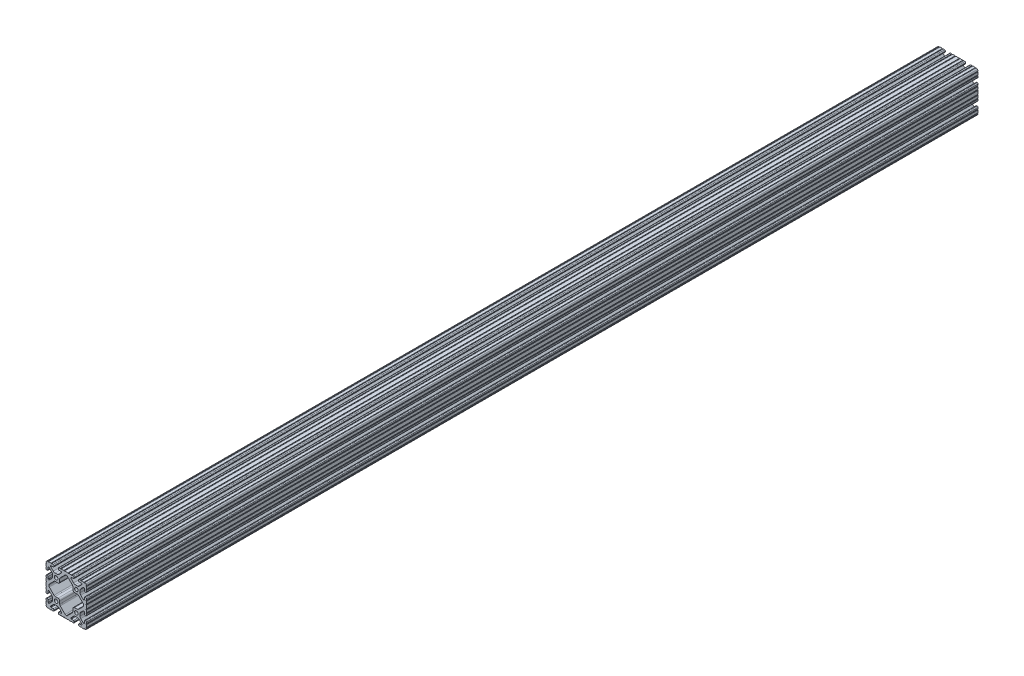
SolidWorks part; units mm, degrees
material "6061-T6 (SS)"
ref_plane "Front" through (0, 0, 0) normal (0, 0, 1) x (1, 0, 0)
ref_plane "Top" through (0, 0, 0) normal (0, 1, 0) x (1, 0, 0)
ref_plane "Right" through (0, 0, 0) normal (1, 0, 0) x (0, 0, -1)
ref_plane "Plane1" through (0, 0, -609.6) normal (0, 0, -1) x (-1, 0, 0)
sketch "Sketch1" plane through (0, 0, -609.6) normal (0, 0, -1) x (-1, 0, 0)
  line L0 (31.9021, -2.4756) -> (23.0141, -11.3637)
  line L1 (20.769, -12.2936) -> (15.4686, -12.2936)
  line L2 (12.2936, -15.4686) -> (12.2936, -20.5983)
  line L3 (11.3637, -22.8433) -> (2.0515, -32.1555)
  line L4 (-2.0515, -32.1555) -> (-11.3637, -22.8433)
  line L5 (-12.2936, -20.5983) -> (-12.2936, -15.4686)
  line L6 (-15.4686, -12.2936) -> (-20.769, -12.2936)
  line L7 (-23.0141, -11.3637) -> (-31.9021, -2.4756)
  line L8 (-31.9021, 2.4756) -> (-23.0141, 11.3637)
  line L9 (-20.769, 12.2936) -> (-15.4686, 12.2936)
  line L10 (-12.2936, 15.4686) -> (-12.2936, 20.5983)
  line L11 (-11.3637, 22.8433) -> (-2.0515, 32.1555)
  line L12 (2.0515, 32.1555) -> (11.3637, 22.8433)
  line L13 (12.2936, 20.5983) -> (12.2936, 15.4686)
  line L14 (15.4686, 12.2936) -> (20.769, 12.2936)
  line L15 (23.0141, 11.3637) -> (31.9021, 2.4756)
  line L16 (36.5252, -23.0554) -> (35.6108, -23.0554)
  line L17 (34.036, -24.6302) -> (34.036, -28.448)
  line L18 (33.147, -29.337) -> (32.6643, -29.337)
  line L19 (32.0357, -29.0766) -> (27.1976, -24.2385)
  line L20 (25.8064, -20.8799) -> (25.8064, -17.2201)
  line L21 (27.1976, -13.8615) -> (31.9489, -9.1101)
  line L22 (32.7869, -8.763) -> (33.0603, -8.763)
  line L23 (34.036, -9.7387) -> (34.036, -13.4698)
  line L24 (35.6108, -15.0446) -> (36.5252, -15.0446)
  line L25 (38.1, -13.4698) -> (38.1, -11.075)
  line L26 (38.1, -9.552) -> (38.1, -4.7238)
  line L27 (38.1, -3.2007) -> (38.1, 3.2007)
  line L28 (38.1, 4.7238) -> (38.1, 9.552)
  line L29 (38.1, 11.075) -> (38.1, 13.4698)
  line L30 (36.5252, 15.0446) -> (35.6108, 15.0446)
  line L31 (34.036, 13.4698) -> (34.036, 9.7387)
  line L32 (33.0603, 8.763) -> (32.7869, 8.763)
  line L33 (31.9489, 9.1101) -> (27.1976, 13.8615)
  line L34 (25.8064, 17.2201) -> (25.8064, 20.8799)
  line L35 (27.1976, 24.2385) -> (32.0357, 29.0766)
  line L36 (32.6643, 29.337) -> (33.147, 29.337)
  line L37 (34.036, 28.448) -> (34.036, 24.6302)
  line L38 (35.6108, 23.0554) -> (36.5252, 23.0554)
  line L39 (38.1, 24.6302) -> (38.1, 27.0238)
  line L40 (38.1, 28.5453) -> (38.1, 33.373)
  line L41 (33.4288, 38.1) -> (28.6011, 38.1)
  line L42 (27.0772, 38.1) -> (24.6888, 38.1)
  line L43 (23.114, 36.5252) -> (23.114, 35.6108)
  line L44 (24.6888, 34.036) -> (28.448, 34.036)
  line L45 (29.337, 33.147) -> (29.337, 32.7207)
  line L46 (29.1002, 31.8885) -> (24.4093, 27.1976)
  line L47 (21.0507, 25.8064) -> (17.0493, 25.8064)
  line L48 (13.6907, 27.1976) -> (9.0234, 31.8649)
  line L49 (8.763, 32.4935) -> (8.763, 33.147)
  line L50 (9.652, 34.036) -> (13.4112, 34.036)
  line L51 (14.986, 35.6108) -> (14.986, 36.5252)
  line L52 (13.4112, 38.1) -> (11.1289, 38.1)
  line L53 (9.6053, 38.1) -> (4.7773, 38.1)
  line L54 (3.2537, 38.1) -> (-3.2537, 38.1)
  line L55 (-4.7773, 38.1) -> (-9.6053, 38.1)
  line L56 (-11.1289, 38.1) -> (-13.4112, 38.1)
  line L57 (-14.986, 36.5252) -> (-14.986, 35.6108)
  line L58 (-13.4112, 34.036) -> (-9.652, 34.036)
  line L59 (-8.763, 33.147) -> (-8.763, 32.4935)
  line L60 (-9.0234, 31.8649) -> (-13.6907, 27.1976)
  line L61 (-17.0493, 25.8064) -> (-21.0507, 25.8064)
  line L62 (-24.4093, 27.1976) -> (-29.1002, 31.8885)
  line L63 (-29.337, 32.7207) -> (-29.337, 33.147)
  line L64 (-28.448, 34.036) -> (-24.6888, 34.036)
  line L65 (-23.114, 35.6108) -> (-23.114, 36.5252)
  line L66 (-24.6888, 38.1) -> (-27.0772, 38.1)
  line L67 (-28.6011, 38.1) -> (-33.4288, 38.1)
  line L68 (-38.1, 33.373) -> (-38.1, 28.5453)
  line L69 (-38.1, 27.0238) -> (-38.1, 24.6302)
  line L70 (-36.5252, 23.0554) -> (-35.6108, 23.0554)
  line L71 (-34.036, 24.6302) -> (-34.036, 28.448)
  line L72 (-33.147, 29.337) -> (-32.6643, 29.337)
  line L73 (-32.0357, 29.0766) -> (-27.1976, 24.2385)
  line L74 (-25.8064, 20.8799) -> (-25.8064, 17.2201)
  line L75 (-27.1976, 13.8615) -> (-31.9489, 9.1101)
  line L76 (-32.7869, 8.763) -> (-33.0603, 8.763)
  line L77 (-34.036, 9.7387) -> (-34.036, 13.4698)
  line L78 (-35.6108, 15.0446) -> (-36.5252, 15.0446)
  line L79 (-38.1, 13.4698) -> (-38.1, 11.075)
  line L80 (-38.1, 9.552) -> (-38.1, 4.7238)
  line L81 (-38.1, 3.2007) -> (-38.1, -3.2007)
  line L82 (-38.1, -4.7238) -> (-38.1, -9.552)
  line L83 (-38.1, -11.075) -> (-38.1, -13.4698)
  line L84 (-36.5252, -15.0446) -> (-35.6108, -15.0446)
  line L85 (-34.036, -13.4698) -> (-34.036, -9.7387)
  line L86 (-33.0603, -8.763) -> (-32.7869, -8.763)
  line L87 (-31.9489, -9.1101) -> (-27.1976, -13.8615)
  line L88 (-25.8064, -17.2201) -> (-25.8064, -20.8799)
  line L89 (-27.1976, -24.2385) -> (-32.0357, -29.0766)
  line L90 (-32.6643, -29.337) -> (-33.147, -29.337)
  line L91 (-34.036, -28.448) -> (-34.036, -24.6302)
  line L92 (-35.6108, -23.0554) -> (-36.5252, -23.0554)
  line L93 (-38.1, -24.6302) -> (-38.1, -27.0238)
  line L94 (-38.1, -28.5453) -> (-38.1, -33.373)
  line L95 (-33.4288, -38.1) -> (-28.6011, -38.1)
  line L96 (-27.0772, -38.1) -> (-24.6888, -38.1)
  line L97 (-23.114, -36.5252) -> (-23.114, -35.6108)
  line L98 (-24.6888, -34.036) -> (-28.448, -34.036)
  line L99 (-29.337, -33.147) -> (-29.337, -32.7207)
  line L100 (-29.1002, -31.8885) -> (-24.4093, -27.1976)
  line L101 (-21.0507, -25.8064) -> (-17.0493, -25.8064)
  line L102 (-13.6907, -27.1976) -> (-9.0234, -31.8649)
  line L103 (-8.763, -32.4935) -> (-8.763, -33.147)
  line L104 (-9.652, -34.036) -> (-13.4112, -34.036)
  line L105 (-14.986, -35.6108) -> (-14.986, -36.5252)
  line L106 (-13.4112, -38.1) -> (-11.1289, -38.1)
  line L107 (-9.6053, -38.1) -> (-4.7773, -38.1)
  line L108 (-3.2537, -38.1) -> (3.2537, -38.1)
  line L109 (4.7773, -38.1) -> (9.6053, -38.1)
  line L110 (11.1289, -38.1) -> (13.4112, -38.1)
  line L111 (14.986, -36.5252) -> (14.986, -35.6108)
  line L112 (13.4112, -34.036) -> (9.652, -34.036)
  line L113 (8.763, -33.147) -> (8.763, -32.4935)
  line L114 (9.0234, -31.8649) -> (13.6907, -27.1976)
  line L115 (17.0493, -25.8064) -> (21.0507, -25.8064)
  line L116 (24.4093, -27.1976) -> (29.1002, -31.8885)
  line L117 (29.337, -32.7207) -> (29.337, -33.147)
  line L118 (28.448, -34.036) -> (24.6888, -34.036)
  line L119 (23.114, -35.6108) -> (23.114, -36.5252)
  line L120 (24.6888, -38.1) -> (27.0772, -38.1)
  line L121 (28.6011, -38.1) -> (33.4288, -38.1)
  line L122 (38.1, -33.373) -> (38.1, -28.5453)
  line L123 (38.1, -27.0238) -> (38.1, -24.6302)
  arc A0 (31.9021, 2.4756) -> (32.7287, 0) centre (29.8367, 0.4102) cw
  arc A1 (32.7287, 0) -> (31.9021, -2.4756) centre (29.8367, -0.4102) cw
  arc A2 (23.0141, -11.3637) -> (20.769, -12.2936) centre (20.769, -9.1186) cw
  arc A3 (15.4686, -12.2936) -> (12.2936, -15.4686) centre (15.4686, -15.4686) ccw
  arc A4 (12.2936, -20.5983) -> (11.3637, -22.8433) centre (9.1186, -20.5983) cw
  arc A5 (2.0515, -32.1555) -> (0, -33.011) centre (-0.0139, -30.09) cw
  arc A6 (0, -33.011) -> (-2.0515, -32.1555) centre (0.0139, -30.09) cw
  arc A7 (-11.3637, -22.8433) -> (-12.2936, -20.5983) centre (-9.1186, -20.5983) cw
  arc A8 (-12.2936, -15.4686) -> (-15.4686, -12.2936) centre (-15.4686, -15.4686) ccw
  arc A9 (-20.769, -12.2936) -> (-23.0141, -11.3637) centre (-20.769, -9.1186) cw
  arc A10 (-31.9021, -2.4756) -> (-32.7287, 0) centre (-29.8367, -0.4102) cw
  arc A11 (-32.7287, 0) -> (-31.9021, 2.4756) centre (-29.8367, 0.4102) cw
  arc A12 (-23.0141, 11.3637) -> (-20.769, 12.2936) centre (-20.769, 9.1186) cw
  arc A13 (-15.4686, 12.2936) -> (-12.2936, 15.4686) centre (-15.4686, 15.4686) ccw
  arc A14 (-12.2936, 20.5983) -> (-11.3637, 22.8433) centre (-9.1186, 20.5983) cw
  arc A15 (-2.0515, 32.1555) -> (0, 33.011) centre (0.0139, 30.09) cw
  arc A16 (0, 33.011) -> (2.0515, 32.1555) centre (-0.0139, 30.09) cw
  arc A17 (11.3637, 22.8433) -> (12.2936, 20.5983) centre (9.1186, 20.5983) cw
  arc A18 (12.2936, 15.4686) -> (15.4686, 12.2936) centre (15.4686, 15.4686) ccw
  arc A19 (20.769, 12.2936) -> (23.0141, 11.3637) centre (20.769, 9.1186) cw
  circle A20 centre (19.05, -19.05) radius 3.3274
  circle A21 centre (19.05, 19.05) radius 3.3274
  circle A22 centre (-19.05, 19.05) radius 3.3274
  circle A23 centre (-19.05, -19.05) radius 3.3274
  arc A24 (38.1, -24.6302) -> (36.5252, -23.0554) centre (36.5252, -24.6302) ccw
  arc A25 (35.6108, -23.0554) -> (34.036, -24.6302) centre (35.6108, -24.6302) ccw
  arc A26 (34.036, -28.448) -> (33.147, -29.337) centre (33.147, -28.448) cw
  arc A27 (32.6643, -29.337) -> (32.0357, -29.0766) centre (32.6643, -28.448) cw
  arc A28 (27.1976, -24.2385) -> (25.8064, -20.8799) centre (30.5562, -20.8799) cw
  arc A29 (25.8064, -17.2201) -> (27.1976, -13.8615) centre (30.5562, -17.2201) cw
  arc A30 (31.9489, -9.1101) -> (32.7869, -8.763) centre (32.7869, -9.9481) cw
  arc A31 (33.0603, -8.763) -> (34.036, -9.7387) centre (33.0603, -9.7387) cw
  arc A32 (34.036, -13.4698) -> (35.6108, -15.0446) centre (35.6108, -13.4698) ccw
  arc A33 (36.5252, -15.0446) -> (38.1, -13.4698) centre (36.5252, -13.4698) ccw
  arc A34 (38.1, -11.075) -> (38.1, -9.552) centre (37.9035, -10.3135) cw
  arc A35 (38.1, -4.7238) -> (38.1, -3.2007) centre (37.9035, -3.9622) cw
  arc A36 (38.1, 3.2007) -> (38.1, 4.7238) centre (37.9035, 3.9622) cw
  arc A37 (38.1, 9.552) -> (38.1, 11.075) centre (37.9035, 10.3135) cw
  arc A38 (38.1, 13.4698) -> (36.5252, 15.0446) centre (36.5252, 13.4698) ccw
  arc A39 (35.6108, 15.0446) -> (34.036, 13.4698) centre (35.6108, 13.4698) ccw
  arc A40 (34.036, 9.7387) -> (33.0603, 8.763) centre (33.0603, 9.7387) cw
  arc A41 (32.7869, 8.763) -> (31.9489, 9.1101) centre (32.7869, 9.9481) cw
  arc A42 (27.1976, 13.8615) -> (25.8064, 17.2201) centre (30.5562, 17.2201) cw
  arc A43 (25.8064, 20.8799) -> (27.1976, 24.2385) centre (30.5562, 20.8799) cw
  arc A44 (32.0357, 29.0766) -> (32.6643, 29.337) centre (32.6643, 28.448) cw
  arc A45 (33.147, 29.337) -> (34.036, 28.448) centre (33.147, 28.448) cw
  arc A46 (34.036, 24.6302) -> (35.6108, 23.0554) centre (35.6108, 24.6302) ccw
  arc A47 (36.5252, 23.0554) -> (38.1, 24.6302) centre (36.5252, 24.6302) ccw
  arc A48 (38.1, 27.0238) -> (38.1, 28.5453) centre (37.9035, 27.7845) cw
  arc A49 (38.1, 33.373) -> (38.1, 34.8455) centre (37.9035, 34.1092) cw
  arc A50 (38.1, 34.8455) -> (37.0861, 37.1826) centre (34.925, 34.8566) ccw
  arc A51 (37.0861, 37.1826) -> (34.9527, 38.1) centre (34.8521, 34.9266) ccw
  arc A52 (34.9527, 38.1) -> (33.4288, 38.1) centre (34.1907, 38.0824) cw
  arc A53 (28.6011, 38.1) -> (27.0772, 38.1) centre (27.8392, 38.0824) cw
  arc A54 (24.6888, 38.1) -> (23.114, 36.5252) centre (24.6888, 36.5252) ccw
  arc A55 (23.114, 35.6108) -> (24.6888, 34.036) centre (24.6888, 35.6108) ccw
  arc A56 (28.448, 34.036) -> (29.337, 33.147) centre (28.448, 33.147) cw
  arc A57 (29.337, 32.7207) -> (29.1002, 31.8885) centre (28.4716, 32.5172) cw
  arc A58 (24.4093, 27.1976) -> (21.0507, 25.8064) centre (21.0507, 30.5562) cw
  arc A59 (17.0493, 25.8064) -> (13.6907, 27.1976) centre (17.0493, 30.5562) cw
  arc A60 (9.0234, 31.8649) -> (8.763, 32.4935) centre (9.652, 32.4935) cw
  arc A61 (8.763, 33.147) -> (9.652, 34.036) centre (9.652, 33.147) cw
  arc A62 (13.4112, 34.036) -> (14.986, 35.6108) centre (13.4112, 35.6108) ccw
  arc A63 (14.986, 36.5252) -> (13.4112, 38.1) centre (13.4112, 36.5252) ccw
  arc A64 (11.1289, 38.1) -> (9.6053, 38.1) centre (10.3671, 38.0824) cw
  arc A65 (4.7773, 38.1) -> (3.2537, 38.1) centre (4.0155, 38.0824) cw
  arc A66 (-3.2537, 38.1) -> (-4.7773, 38.1) centre (-4.0155, 38.0824) cw
  arc A67 (-9.6053, 38.1) -> (-11.1289, 38.1) centre (-10.3671, 38.0824) cw
  arc A68 (-13.4112, 38.1) -> (-14.986, 36.5252) centre (-13.4112, 36.5252) ccw
  arc A69 (-14.986, 35.6108) -> (-13.4112, 34.036) centre (-13.4112, 35.6108) ccw
  arc A70 (-9.652, 34.036) -> (-8.763, 33.147) centre (-9.652, 33.147) cw
  arc A71 (-8.763, 32.4935) -> (-9.0234, 31.8649) centre (-9.652, 32.4935) cw
  arc A72 (-13.6907, 27.1976) -> (-17.0493, 25.8064) centre (-17.0493, 30.5562) cw
  arc A73 (-21.0507, 25.8064) -> (-24.4093, 27.1976) centre (-21.0507, 30.5562) cw
  arc A74 (-29.1002, 31.8885) -> (-29.337, 32.7207) centre (-28.4716, 32.5172) cw
  arc A75 (-29.337, 33.147) -> (-28.448, 34.036) centre (-28.448, 33.147) cw
  arc A76 (-24.6888, 34.036) -> (-23.114, 35.6108) centre (-24.6888, 35.6108) ccw
  arc A77 (-23.114, 36.5252) -> (-24.6888, 38.1) centre (-24.6888, 36.5252) ccw
  arc A78 (-27.0772, 38.1) -> (-28.6011, 38.1) centre (-27.8392, 38.0824) cw
  arc A79 (-33.4288, 38.1) -> (-34.9527, 38.1) centre (-34.1907, 38.0824) cw
  arc A80 (-34.9527, 38.1) -> (-37.0861, 37.1826) centre (-34.8521, 34.9266) ccw
  arc A81 (-37.0861, 37.1826) -> (-38.1, 34.8455) centre (-34.925, 34.8566) ccw
  arc A82 (-38.1, 34.8455) -> (-38.1, 33.373) centre (-37.9035, 34.1092) cw
  arc A83 (-38.1, 28.5453) -> (-38.1, 27.0238) centre (-37.9035, 27.7845) cw
  arc A84 (-38.1, 24.6302) -> (-36.5252, 23.0554) centre (-36.5252, 24.6302) ccw
  arc A85 (-35.6108, 23.0554) -> (-34.036, 24.6302) centre (-35.6108, 24.6302) ccw
  arc A86 (-34.036, 28.448) -> (-33.147, 29.337) centre (-33.147, 28.448) cw
  arc A87 (-32.6643, 29.337) -> (-32.0357, 29.0766) centre (-32.6643, 28.448) cw
  arc A88 (-27.1976, 24.2385) -> (-25.8064, 20.8799) centre (-30.5562, 20.8799) cw
  arc A89 (-25.8064, 17.2201) -> (-27.1976, 13.8615) centre (-30.5562, 17.2201) cw
  arc A90 (-31.9489, 9.1101) -> (-32.7869, 8.763) centre (-32.7869, 9.9481) cw
  arc A91 (-33.0603, 8.763) -> (-34.036, 9.7387) centre (-33.0603, 9.7387) cw
  arc A92 (-34.036, 13.4698) -> (-35.6108, 15.0446) centre (-35.6108, 13.4698) ccw
  arc A93 (-36.5252, 15.0446) -> (-38.1, 13.4698) centre (-36.5252, 13.4698) ccw
  arc A94 (-38.1, 11.075) -> (-38.1, 9.552) centre (-37.9035, 10.3135) cw
  arc A95 (-38.1, 4.7238) -> (-38.1, 3.2007) centre (-37.9035, 3.9622) cw
  arc A96 (-38.1, -3.2007) -> (-38.1, -4.7238) centre (-37.9035, -3.9622) cw
  arc A97 (-38.1, -9.552) -> (-38.1, -11.075) centre (-37.9035, -10.3135) cw
  arc A98 (-38.1, -13.4698) -> (-36.5252, -15.0446) centre (-36.5252, -13.4698) ccw
  arc A99 (-35.6108, -15.0446) -> (-34.036, -13.4698) centre (-35.6108, -13.4698) ccw
  arc A100 (-34.036, -9.7387) -> (-33.0603, -8.763) centre (-33.0603, -9.7387) cw
  arc A101 (-32.7869, -8.763) -> (-31.9489, -9.1101) centre (-32.7869, -9.9481) cw
  arc A102 (-27.1976, -13.8615) -> (-25.8064, -17.2201) centre (-30.5562, -17.2201) cw
  arc A103 (-25.8064, -20.8799) -> (-27.1976, -24.2385) centre (-30.5562, -20.8799) cw
  arc A104 (-32.0357, -29.0766) -> (-32.6643, -29.337) centre (-32.6643, -28.448) cw
  arc A105 (-33.147, -29.337) -> (-34.036, -28.448) centre (-33.147, -28.448) cw
  arc A106 (-34.036, -24.6302) -> (-35.6108, -23.0554) centre (-35.6108, -24.6302) ccw
  arc A107 (-36.5252, -23.0554) -> (-38.1, -24.6302) centre (-36.5252, -24.6302) ccw
  arc A108 (-38.1, -27.0238) -> (-38.1, -28.5453) centre (-37.9035, -27.7845) cw
  arc A109 (-38.1, -33.373) -> (-38.1, -34.8455) centre (-37.9035, -34.1092) cw
  arc A110 (-38.1, -34.8455) -> (-37.0861, -37.1826) centre (-34.925, -34.8566) ccw
  arc A111 (-37.0861, -37.1826) -> (-34.9527, -38.1) centre (-34.8521, -34.9266) ccw
  arc A112 (-34.9527, -38.1) -> (-33.4288, -38.1) centre (-34.1907, -38.0824) cw
  arc A113 (-28.6011, -38.1) -> (-27.0772, -38.1) centre (-27.8392, -38.0824) cw
  arc A114 (-24.6888, -38.1) -> (-23.114, -36.5252) centre (-24.6888, -36.5252) ccw
  arc A115 (-23.114, -35.6108) -> (-24.6888, -34.036) centre (-24.6888, -35.6108) ccw
  arc A116 (-28.448, -34.036) -> (-29.337, -33.147) centre (-28.448, -33.147) cw
  arc A117 (-29.337, -32.7207) -> (-29.1002, -31.8885) centre (-28.4716, -32.5172) cw
  arc A118 (-24.4093, -27.1976) -> (-21.0507, -25.8064) centre (-21.0507, -30.5562) cw
  arc A119 (-17.0493, -25.8064) -> (-13.6907, -27.1976) centre (-17.0493, -30.5562) cw
  arc A120 (-9.0234, -31.8649) -> (-8.763, -32.4935) centre (-9.652, -32.4935) cw
  arc A121 (-8.763, -33.147) -> (-9.652, -34.036) centre (-9.652, -33.147) cw
  arc A122 (-13.4112, -34.036) -> (-14.986, -35.6108) centre (-13.4112, -35.6108) ccw
  arc A123 (-14.986, -36.5252) -> (-13.4112, -38.1) centre (-13.4112, -36.5252) ccw
  arc A124 (-11.1289, -38.1) -> (-9.6053, -38.1) centre (-10.3671, -38.0824) cw
  arc A125 (-4.7773, -38.1) -> (-3.2537, -38.1) centre (-4.0155, -38.0824) cw
  arc A126 (3.2537, -38.1) -> (4.7773, -38.1) centre (4.0155, -38.0824) cw
  arc A127 (9.6053, -38.1) -> (11.1289, -38.1) centre (10.3671, -38.0824) cw
  arc A128 (13.4112, -38.1) -> (14.986, -36.5252) centre (13.4112, -36.5252) ccw
  arc A129 (14.986, -35.6108) -> (13.4112, -34.036) centre (13.4112, -35.6108) ccw
  arc A130 (9.652, -34.036) -> (8.763, -33.147) centre (9.652, -33.147) cw
  arc A131 (8.763, -32.4935) -> (9.0234, -31.8649) centre (9.652, -32.4935) cw
  arc A132 (13.6907, -27.1976) -> (17.0493, -25.8064) centre (17.0493, -30.5562) cw
  arc A133 (21.0507, -25.8064) -> (24.4093, -27.1976) centre (21.0507, -30.5562) cw
  arc A134 (29.1002, -31.8885) -> (29.337, -32.7207) centre (28.4716, -32.5172) cw
  arc A135 (29.337, -33.147) -> (28.448, -34.036) centre (28.448, -33.147) cw
  arc A136 (24.6888, -34.036) -> (23.114, -35.6108) centre (24.6888, -35.6108) ccw
  arc A137 (23.114, -36.5252) -> (24.6888, -38.1) centre (24.6888, -36.5252) ccw
  arc A138 (27.0772, -38.1) -> (28.6011, -38.1) centre (27.8392, -38.0824) cw
  arc A139 (33.4288, -38.1) -> (34.9527, -38.1) centre (34.1907, -38.0824) cw
  arc A140 (34.9527, -38.1) -> (37.0861, -37.1826) centre (34.8521, -34.9266) ccw
  arc A141 (37.0861, -37.1826) -> (38.1, -34.8455) centre (34.925, -34.8566) ccw
  arc A142 (38.1, -34.8455) -> (38.1, -33.373) centre (37.9035, -34.1092) cw
  arc A143 (38.1, -28.5453) -> (38.1, -27.0238) centre (37.9035, -27.7845) cw
extrude "Boss-Extrude1" add sketch "Sketch1" against normal blind 1676.4
